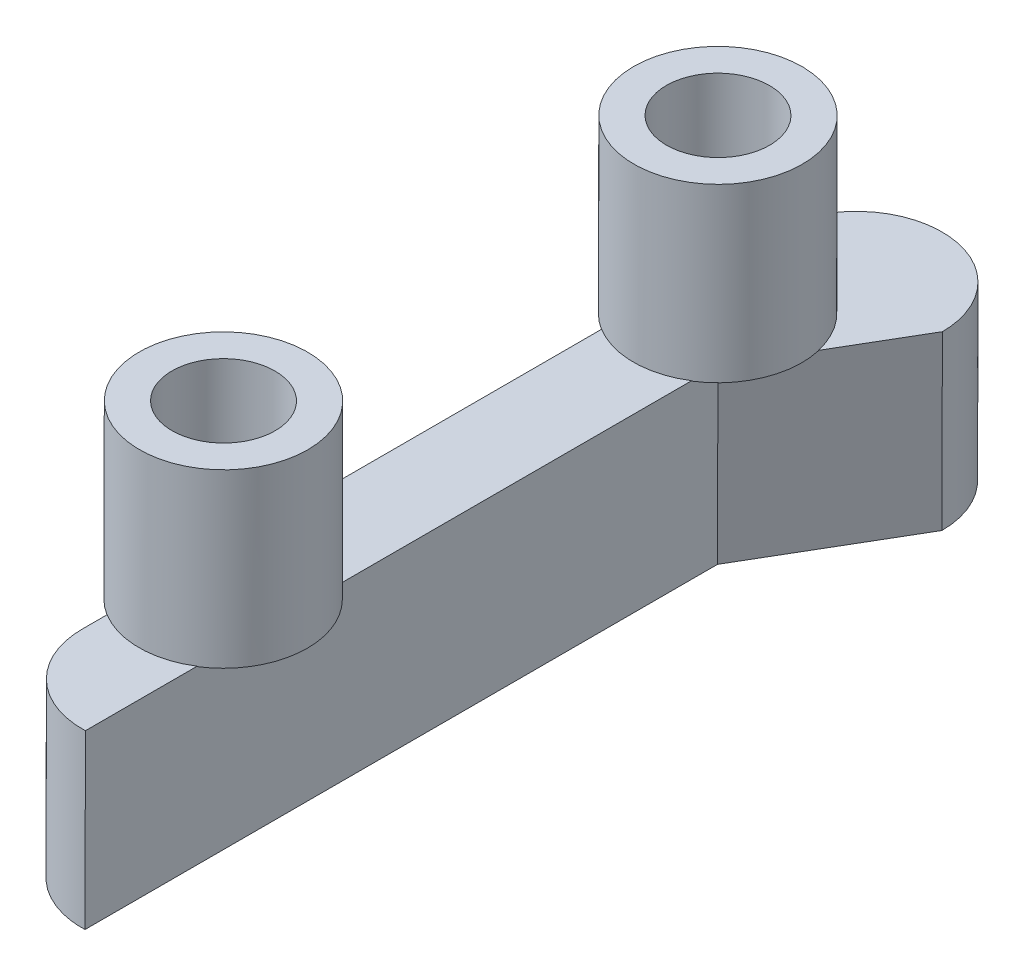
SolidWorks part; units mm, degrees
ref_plane "Front Plane" through (0, 0, 0) normal (0, 0, 1) x (1, 0, 0)
ref_plane "Top Plane" through (0, 0, 0) normal (0, 1, 0) x (1, 0, 0)
ref_plane "Right Plane" through (0, 0, 0) normal (1, 0, 0) x (0, 0, -1)
ref_plane "Plane1" through (0.2124, 88.2612, 0) normal (0.0024, 1, 0) x (1, -0.0024, 0)
sketch "Sketch1" plane through (0.2124, 88.2612, 0) normal (0.0024, 1, 0) x (1, -0.0024, 0)
  line L0 (57.0987, -271.5533) -> (57.0987, -288.7007) construction
  line L1 (57.0987, -271.5533) -> (57.0987, -288.7007)
  line L6 (62.0987, -271.5533) -> (62.0987, -291.5533)
  line L7 (59.6958, -275.6724) -> (62.0987, -271.5533)
  line L8 (59.6958, -295.6724) -> (59.6958, -275.6724)
  line L9 (62.0987, -291.5533) -> (59.6958, -295.6724)
  line L10 (62.0987, -271.5533) -> (62.0987, -291.5533)
  line L11 (59.6958, -275.6724) -> (62.0987, -271.5533)
  line L12 (59.6958, -295.6724) -> (59.6958, -275.6724)
  line L13 (62.0987, -291.5533) -> (59.6958, -295.6724)
  spline S0 degree 3 poles (74.2714, -14284.9704) (55.1287, -54.2949) (54.712, -260.9818) (54.7603, -296.7656) (54.7607, -297.0249) (54.7619, -297.7783) (54.7628, -298.2482) (54.7649, -299.1211) (54.7661, -299.5125) (54.7679, -300.0307) (54.7685, -300.1921) (54.7698, -300.4919) (54.7705, -300.631) (54.7725, -301.0078) (54.7739, -301.2046) (54.776, -301.4206) (54.7767, -301.4792) (54.7782, -301.5694) (54.779, -301.6009) (54.7812, -301.6521) (54.7826, -301.6303) (54.7848, -301.515) (54.7855, -301.4627) (54.787, -301.3296) (54.7877, -301.249) (54.7898, -300.9694) (54.7912, -300.7318) (54.7938, -300.1538) (54.795, -299.8105) (54.7973, -299.0466) (54.7984, -298.6237) (54.7998, -297.9268) (54.8003, -297.6828) (54.8011, -297.1826) (54.8015, -296.9258) (54.8026, -296.1356) (54.8033, -295.5826) (54.804, -294.7126) (54.8042, -294.4169) (54.8046, -293.8239) (54.8047, -293.5252) (54.8051, -292.6227) (54.8052, -292.0106) (54.8051, -290.7765) (54.805, -290.1699) (54.8045, -289.2751) (54.8043, -288.9793) (54.8039, -288.3931) (54.8036, -288.1014) (54.8028, -287.2475) (54.8021, -286.7011) (54.8005, -285.6678) (54.7995, -285.1892) (54.798, -284.5267) (54.7975, -284.3152) (54.7964, -283.911) (54.7958, -283.7178) (54.794, -283.1779) (54.7927, -282.8674) (54.7908, -282.4745) (54.7901, -282.3557) (54.7887, -282.1432) (54.788, -282.0502) (54.7858, -281.8142) (54.7844, -281.7118) (54.7815, -281.6165) (54.78, -281.625) (54.777, -281.753) (54.7756, -281.8714) (54.7735, -282.1316) (54.7728, -282.2328) (54.7714, -282.4597) (54.7707, -282.5855) (54.7688, -282.9991) (54.7675, -283.3228) (54.7657, -283.8827) (54.7652, -284.0814) (54.7641, -284.4956) (54.7636, -284.7121) (54.7621, -285.389) (54.7612, -285.8775) (54.7596, -286.9286) (54.759, -287.4759) (54.7582, -288.3282) (54.758, -288.6176) (54.7576, -289.2072) (54.7574, -289.5089) (54.576, -692.9549) (115.528, -2312.4107) (-708.9989, 13685.6876) knots -2.058294 -2.058294 -2.058294 -2.058294 0.015625 0.015625 0.03125 0.03125 0.0625 0.0625 0.09375 0.09375 0.109375 0.109375 0.125 0.125 0.15625 0.15625 0.171875 0.171875 0.1875 0.1875 0.21875 0.21875 0.234375 0.234375 0.25 0.25 0.28125 0.28125 0.3125 0.3125 0.34375 0.34375 0.359375 0.359375 0.375 0.375 0.40625 0.40625 0.421875 0.421875 0.4375 0.4375 0.46875 0.46875 0.5 0.5 0.515625 0.515625 0.53125 0.53125 0.5625 0.5625 0.59375 0.59375 0.609375 0.609375 0.625 0.625 0.65625 0.65625 0.671875 0.671875 0.6875 0.6875 0.71875 0.71875 0.75 0.75 0.78125 0.78125 0.796875 0.796875 0.8125 0.8125 0.84375 0.84375 0.859375 0.859375 0.875 0.875 0.90625 0.90625 0.9375 0.9375 0.953125 0.953125 0.96875 0.96875 21.802605 21.802605 21.802605 21.802605 only from (57.0987, -291.5533) to (57.0987, -288.7007) construction
  spline S1 degree 3 poles (-1910.3781, 36.9604) (-247.8118, -203.0495) (66.5392, -269.2251) (62.0205, -292.1946) (61.9736, -292.3503) (61.7926, -292.7938) (61.6134, -293.0678) (61.166, -293.5272) (60.8911, -293.7187) (60.4356, -293.9148) (60.2729, -293.9666) (59.9413, -294.0355) (59.7733, -294.053) (59.4329, -294.0536) (59.2605, -294.0361) (58.9299, -293.9681) (58.7677, -293.9171) (58.4602, -293.7853) (58.3161, -293.7055) (58.0458, -293.5194) (57.9204, -293.4132) (57.5835, -293.0674) (57.4046, -292.7935) (57.2236, -292.3498) (57.1767, -292.1937) (52.4327, -268.0389) (401.1252, -199.0816) (2032.0992, 21.2723) knots -8.918573 -8.918573 -8.918573 -8.918573 0.0625 0.0625 0.125 0.125 0.25 0.25 0.375 0.375 0.4375 0.4375 0.5 0.5 0.5625 0.5625 0.625 0.625 0.6875 0.6875 0.75 0.75 0.875 0.875 0.9375 0.9375 10.39234 10.39234 10.39234 10.39234 only from (62.0987, -291.5533) to (57.0987, -291.5533) construction
  spline S2 degree 3 poles (2060.5072, -278.104) (-714.938, -386.1273) (69.1289, -306.7061) (62.0187, -270.9049) (61.9708, -270.7472) (61.8462, -270.4464) (61.7686, -270.3008) (61.5861, -270.0278) (61.4828, -269.9021) (61.2526, -269.6715) (61.1242, -269.5659) (60.8529, -269.3845) (60.7095, -269.3076) (60.4069, -269.1819) (60.2482, -269.1336) (59.9286, -269.0698) (59.766, -269.0534) (59.4354, -269.0532) (59.2729, -269.0693) (58.9531, -269.1326) (58.7941, -269.1807) (58.4914, -269.3059) (58.3478, -269.3826) (58.076, -269.5638) (57.9474, -269.6692) (57.6017, -270.0144) (57.4153, -270.2929) (51.9934, -283.3333) (151.5758, -346.1818) (979.9657, 1500.3149) knots -13.735207 -13.735207 -13.735207 -13.735207 0.0625 0.0625 0.125 0.125 0.1875 0.1875 0.25 0.25 0.3125 0.3125 0.375 0.375 0.4375 0.4375 0.5 0.5 0.5625 0.5625 0.625 0.625 0.6875 0.6875 0.75 0.75 0.875 0.875 6.172444 6.172444 6.172444 6.172444 only from (62.0987, -271.5533) to (57.0987, -271.5533) construction
  spline S3 degree 3 poles (57.0987, -291.5533) (57.0987, -291.5) (57.0987, -291.4467) (57.0989, -290.776) (57.099, -290.169) (57.0989, -289.2792) (57.0988, -288.9887) (57.0987, -288.7007) knots 0.46605 0.46605 0.46605 0.46605 0.46875 0.46875 0.5 0.5 0.515337 0.515337 0.515337 0.515337
  spline S4 degree 3 poles (62.0987, -291.5533) (62.0987, -291.7163) (62.0829, -291.8771) (62.0205, -292.1946) (61.9736, -292.3503) (61.7926, -292.7938) (61.6134, -293.0678) (61.166, -293.5272) (60.8911, -293.7187) (60.4356, -293.9148) (60.2729, -293.9666) (59.9413, -294.0355) (59.7733, -294.053) (59.4329, -294.0536) (59.2605, -294.0361) (58.9299, -293.9681) (58.7677, -293.9171) (58.4602, -293.7853) (58.3161, -293.7055) (58.0458, -293.5194) (57.9204, -293.4132) (57.5835, -293.0674) (57.4046, -292.7935) (57.2236, -292.3498) (57.1767, -292.1937) (57.1144, -291.8765) (57.0987, -291.7159) (57.0987, -291.5533) knots 0 0 0 0 0.0625 0.0625 0.125 0.125 0.25 0.25 0.375 0.375 0.4375 0.4375 0.5 0.5 0.5625 0.5625 0.625 0.625 0.6875 0.6875 0.75 0.75 0.875 0.875 0.9375 0.9375 1 1 1 1
  spline S5 degree 3 poles (62.0987, -271.5533) (62.0987, -271.3901) (62.0829, -271.2277) (62.0187, -270.9049) (61.9708, -270.7472) (61.8462, -270.4464) (61.7686, -270.3008) (61.5861, -270.0278) (61.4828, -269.9021) (61.2526, -269.6715) (61.1242, -269.5659) (60.8529, -269.3845) (60.7095, -269.3076) (60.4069, -269.1819) (60.2482, -269.1336) (59.9286, -269.0698) (59.766, -269.0534) (59.4354, -269.0532) (59.2729, -269.0693) (58.9531, -269.1326) (58.7941, -269.1807) (58.4914, -269.3059) (58.3478, -269.3826) (58.076, -269.5638) (57.9474, -269.6692) (57.6017, -270.0144) (57.4153, -270.2929) (57.1653, -270.8941) (57.0987, -271.2226) (57.0987, -271.5533) knots 0 0 0 0 0.0625 0.0625 0.125 0.125 0.1875 0.1875 0.25 0.25 0.3125 0.3125 0.375 0.375 0.4375 0.4375 0.5 0.5 0.5625 0.5625 0.625 0.625 0.6875 0.6875 0.75 0.75 0.875 0.875 1 1 1 1
  dimension "D1" = 0
extrude "Boss-Extrude1" add sketch "Sketch1" against normal blind 5 and the other way blind 0.01
sketch "Sketch5" plane through (0.2124, 88.2612, 0) normal (0.0024, 1, 0) x (1, -0.0024, 0)
  line L0 (58.3824, -274.3691) -> (58.3824, -288.7375) construction
  line L1 (58.3824, -293.7375) -> (58.3824, -269.3691) construction
  line L9 (59.6662, -281.5533) -> (57.0987, -281.5533) construction
  line L10 (59.6662, -275.6724) -> (59.6662, -291.6335) construction
  line L11 (57.0987, -271.5533) -> (57.0987, -288.7007) construction
  circle A6 centre (58.3824, -274.3691) radius 2.45
  circle A7 centre (58.3824, -274.3691) radius 1.5
  circle A8 centre (58.3824, -288.7375) radius 2.45
  circle A9 centre (58.3824, -288.7375) radius 1.5
  spline S2 degree 3 poles (59.6958, -294.0514) (59.665, -294.0526) (59.6341, -294.0532) (59.4329, -294.0536) (59.2605, -294.0361) (58.9299, -293.9681) (58.7677, -293.9171) (58.4602, -293.7853) (58.3161, -293.7055) (58.0458, -293.5194) (57.9204, -293.4132) (57.5835, -293.0674) (57.4046, -292.7935) (57.2236, -292.3498) (57.1767, -292.1937) (57.1144, -291.8765) (57.0987, -291.7159) (57.0987, -291.5533) knots 0.488632 0.488632 0.488632 0.488632 0.5 0.5 0.5625 0.5625 0.625 0.625 0.6875 0.6875 0.75 0.75 0.875 0.875 0.9375 0.9375 1 1 1 1 construction
  spline S3 degree 3 poles (62.0987, -271.5533) (62.0987, -271.3901) (62.0829, -271.2277) (62.0187, -270.9049) (61.9708, -270.7472) (61.8462, -270.4464) (61.7686, -270.3008) (61.5861, -270.0278) (61.4828, -269.9021) (61.2526, -269.6715) (61.1242, -269.5659) (60.8529, -269.3845) (60.7095, -269.3076) (60.4069, -269.1819) (60.2482, -269.1336) (59.9286, -269.0698) (59.766, -269.0534) (59.4354, -269.0532) (59.2729, -269.0693) (58.9531, -269.1326) (58.7941, -269.1807) (58.4914, -269.3059) (58.3478, -269.3826) (58.076, -269.5638) (57.9474, -269.6692) (57.6017, -270.0144) (57.4153, -270.2929) (57.1653, -270.8941) (57.0987, -271.2226) (57.0987, -271.5533) knots 0 0 0 0 0.0625 0.0625 0.125 0.125 0.1875 0.1875 0.25 0.25 0.3125 0.3125 0.375 0.375 0.4375 0.4375 0.5 0.5 0.5625 0.5625 0.625 0.625 0.6875 0.6875 0.75 0.75 0.875 0.875 1 1 1 1 construction
  point P20 (58.3824, -281.5533)
  point P21 (58.3824, -281.5533)
  dimension "D1" = 4.9
  dimension "D2" = 3
  dimension "D3" = 5
extrude "Boss-Extrude2" add sketch "Sketch5" along normal blind 5
